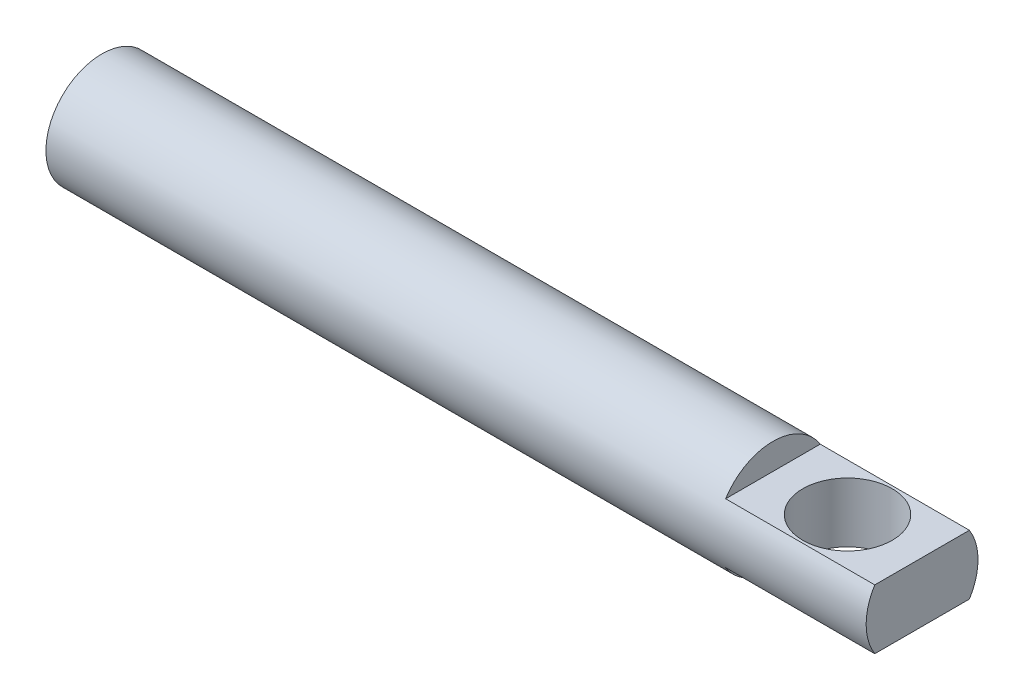
SolidWorks part; units mm, degrees
ref_plane "Front Plane" through (0, 0, 0) normal (0, 0, 1) x (1, 0, 0)
ref_plane "Top Plane" through (0, 0, 0) normal (0, 1, 0) x (1, 0, 0)
ref_plane "Right Plane" through (0, 0, 0) normal (1, 0, 0) x (0, 0, -1)
sketch "Sketch1" plane through (0, 0, 0) normal (1, 0, 0) x (0, 0, -1)
  circle A1 centre (0, 0) radius 3.75
extrude "Boss-Extrude1" add sketch "Sketch1" along normal blind 45
sketch "Sketch2" plane through (45, 0, 0) normal (1, 0, 0) x (0, 0, -1)
  line L1 (0, 2) -> (-3.1721, 2)
  line L3 (-3.1721, -2) -> (3.1721, -2)
  line L5 (3.1721, 2) -> (0, 2)
  circle A1 centre (0, 0) radius 3.75
  arc A2 (-3.1721, 2) -> (3.1721, 2) centre (0, 0) ccw
  circle M2 centre (0, 0) radius 3.75
  dimension "D1" = 0
extrude "Boss-Extrude2" add sketch "Sketch2" along normal blind 10 contours L5 L1 L3 M2
sketch "Sketch3" plane through (0, 2, 0) normal (0, 1, 0) x (1, 0, 0)
  circle A0 centre (50, 0) radius 3
extrude "Cut-Extrude1" cut sketch "Sketch3" against normal blind 10
